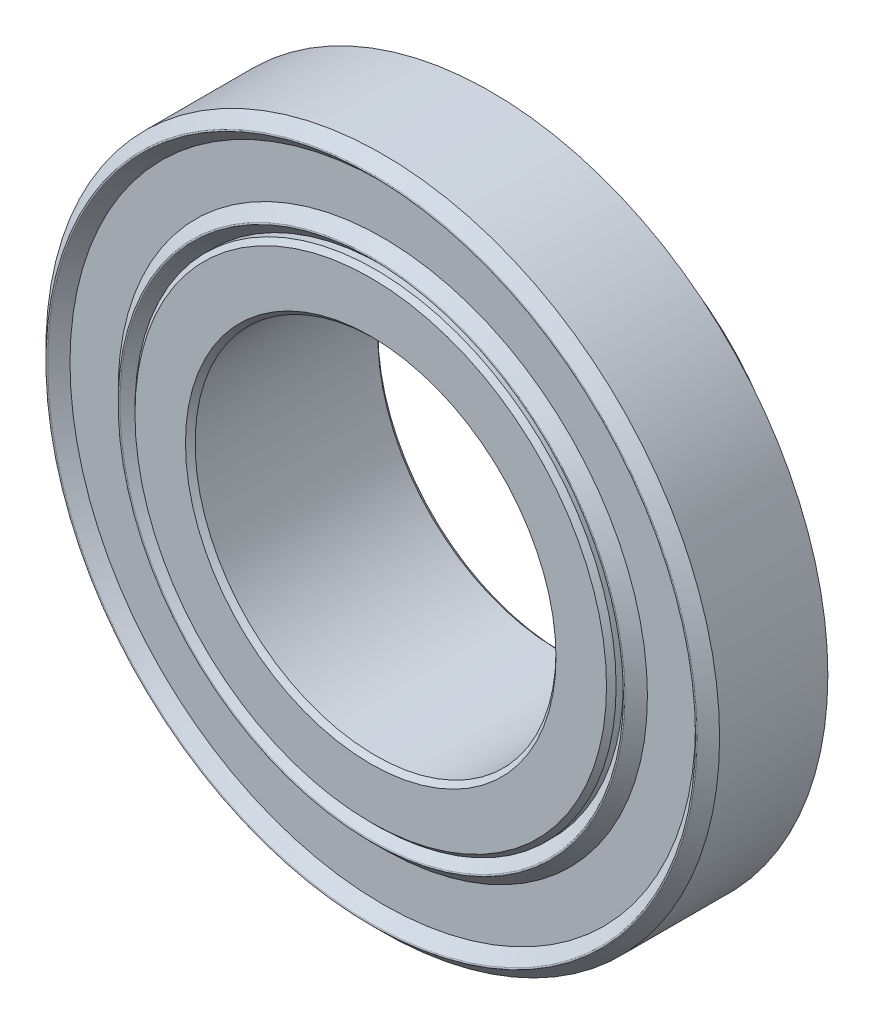
SolidWorks part; units mm, degrees
ref_plane "前基準面" through (0, 0, 0) normal (0, 0, 1) x (1, 0, 0)
ref_plane "上基準面" through (0, 0, 0) normal (0, 1, 0) x (1, 0, 0)
ref_plane "右基準面" through (0, 0, 0) normal (1, 0, 0) x (0, 0, -1)
sketch "草圖2" plane through (0, 0, 0) normal (0, 1, 0) x (1, 0, 0)
  line L0 (0, 0) -> (0, 13.9333) construction
  line L1 (10, 5) -> (14, 5)
  line L2 (10, 5) -> (10, 0.5)
  line L4 (14, 5) -> (14, 0.5)
  line L5 (11, 0.5) -> (13, 0.5)
  line L6 (10, 0.5) -> (10.4646, 0.0354)
  line L7 (10.5354, 0.0354) -> (11, 0.5)
  line L8 (14, 0.5) -> (13.5354, 0.0354)
  line L9 (13.4646, 0.0354) -> (13, 0.5)
  arc A0 (13.5354, 0.0354) -> (13.4646, 0.0354) centre (13.5, 0.0707) cw
  arc A1 (10.5354, 0.0354) -> (10.4646, 0.0354) centre (10.5, 0.0707) cw
  point P9 (13.5, 0)
  point P16 (10.5, 0)
  dimension "D1" = 0.05
  dimension "D2" = 14
  dimension "D3" = 10
  dimension "D5" = 1
  dimension "D6" = 1
  dimension "D7" = 0.5
  dimension "D8" = 0.5
revolve "旋轉1" add sketch "草圖2" angle 360 about L0
sketch "草圖4" plane through (0, 0, 0) normal (0, 0, 1) x (1, 0, 0)
  circle A0 centre (0, 0) radius 10
  circle A1 centre (0, 0) radius 7.5
  dimension "D1" = 15
extrude "填料-伸長1" add sketch "草圖4" against normal blind 8 separate body
chamfer "導角1" distance 0.2 angle 45 4 edges at (7.5, 0, -8) (10, 0, -8) (7.5, 0, 0) (10, 0, 0)
